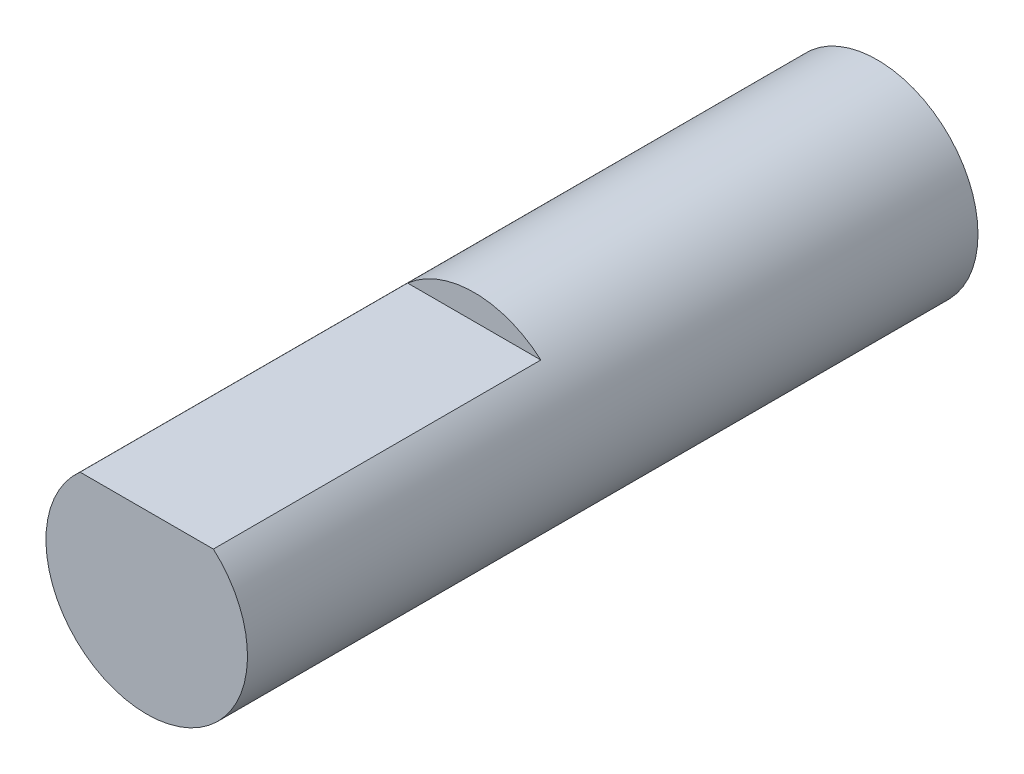
SolidWorks part; units mm, degrees
ref_plane "정면" through (0, 0, 0) normal (0, 0, 1) x (1, 0, 0)
ref_plane "윗면" through (0, 0, 0) normal (0, 1, 0) x (1, 0, 0)
ref_plane "우측면" through (0, 0, 0) normal (1, 0, 0) x (0, 0, -1)
sketch "스케치1" plane through (0, 0, 0) normal (0, 0, 1) x (1, 0, 0)
  circle A0 centre (0, 0) radius 4
  dimension "D1" = 8
extrude "보스-돌출1" add sketch "스케치1" along normal blind 29
sketch "스케치2" plane through (0, 0, 29) normal (0, 0, 1) x (1, 0, 0)
  line L0 (-2.6458, 3) -> (2.6458, 3)
  arc A0 (-2.6458, 3) -> (2.6458, 3) centre (0, 0) cw
  circle A1 centre (0, 0) radius 4 construction
  dimension "D1" = 3
extrude "컷-돌출1" cut sketch "스케치2" against normal blind 13
